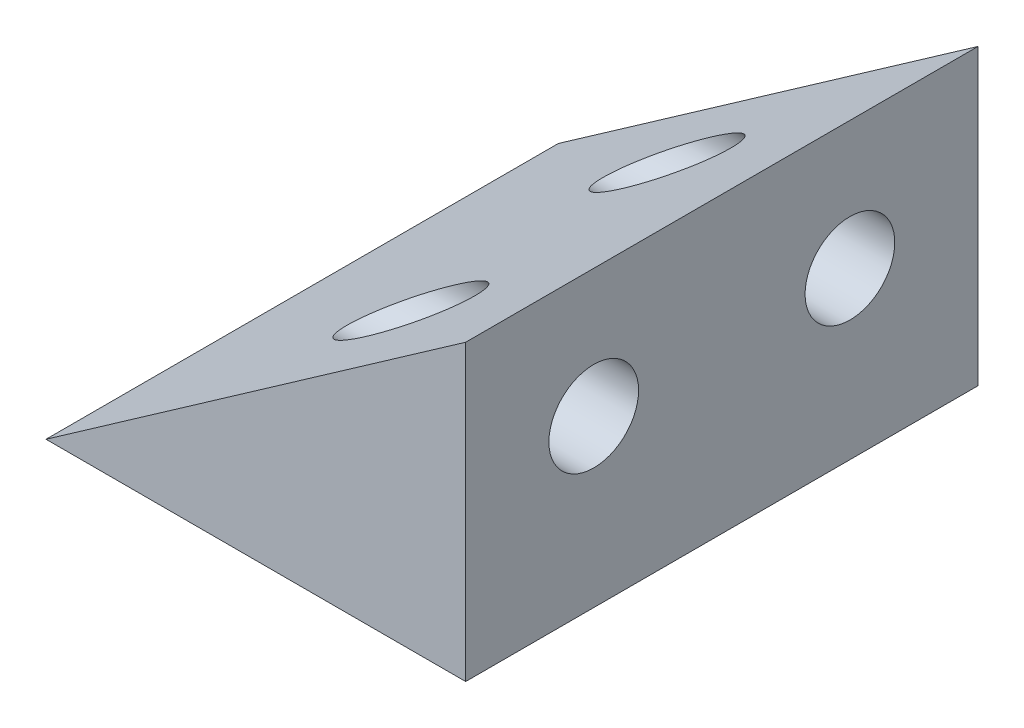
SolidWorks part; units mm, degrees
ref_plane "Front Plane" through (0, 0, 0) normal (0, 0, 1) x (1, 0, 0)
ref_plane "Top Plane" through (0, 0, 0) normal (0, 1, 0) x (1, 0, 0)
ref_plane "Right Plane" through (0, 0, 0) normal (1, 0, 0) x (0, 0, -1)
sketch "Sketch1" plane through (0, 0, 0) normal (0, 0, 1) x (1, 0, 0)
  line L0 (0, 0) -> (-16.383, 0)
  line L1 (-16.383, 0) -> (0, 11.4715)
  line L2 (0, 11.4715) -> (0, 0)
  dimension "D1" = 20
  dimension "D2" = 35
extrude "Boss-Extrude1" add sketch "Sketch1" along normal blind 20
sketch "Sketch2" plane through (-5.3899, 7.6975, 0) normal (-0.5736, 0.8192, 0) x (0, 0, 1)
  line L0 (20, 6.5798) -> (0, 6.5798) construction
  line L1 (20, 6.5798) -> (20, -13.4202) construction
  line L2 (0, -3.4202) -> (20, -3.4202) construction
  line L3 (0, 6.5798) -> (0, -13.4202) construction
  line L4 (10, 6.5798) -> (10, -13.4202) construction
  line L5 (20, -13.4202) -> (0, -13.4202) construction
sketch "Sketch3" plane through (0, 0, 0) normal (1, 0, 0) x (0, 0, -1)
  line L0 (-10, 11.4715) -> (-10, 0) construction
  line L1 (-20, 11.4715) -> (0, 11.4715) construction
  line L3 (-20, 5.7358) -> (0, 5.7358) construction
  line L4 (0, 0) -> (0, 11.4715) construction
  circle A1 centre (-5, 6.4715) radius 1.75
  circle A2 centre (-15, 6.4715) radius 1.75
  dimension "D1" = 3.5
  dimension "D2" = 5
  dimension "D3" = 5
extrude "Cut-Extrude1" cut sketch "Sketch3" along direction (-1, 0, 0) on the side against the normal up to surface (4.6415 mm away)
sketch "Sketch4" plane through (0, 0, 0) normal (0, -1, 0) x (1, 0, 0)
  line L0 (-8.1915, 0) -> (-8.1915, 20) construction
  line L1 (-16.383, 0) -> (0, 0) construction
  line L2 (-16.383, 20) -> (0, 20) construction
  text T0 "35\r\n" font "Century Gothic" height 3.5
extrude "Cut-Extrude2" cut sketch "Sketch4" against normal blind 1
